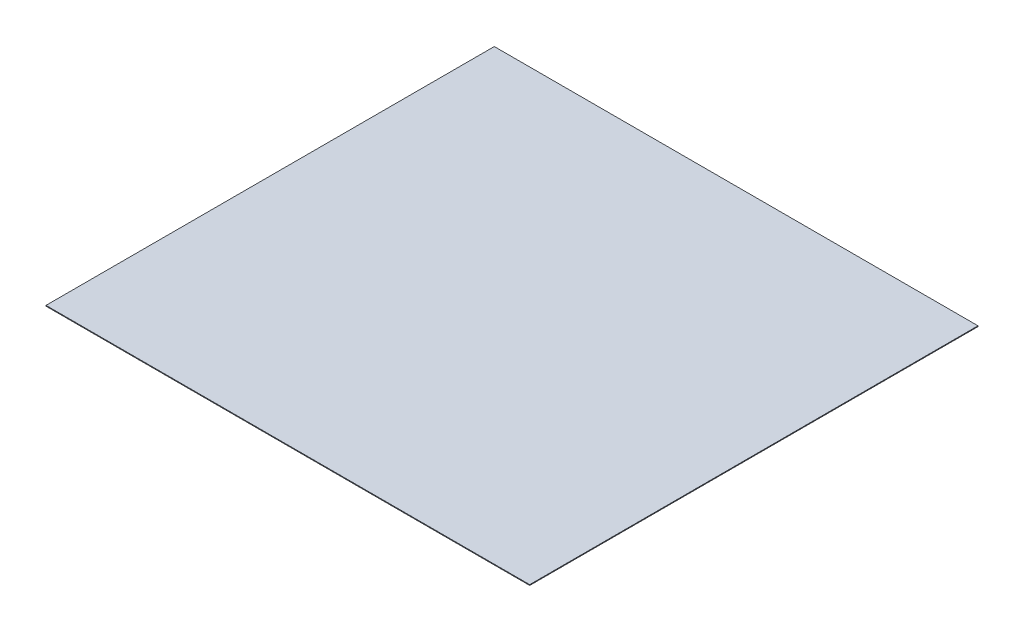
SolidWorks part; units mm, degrees
ref_plane "Front Plane" through (0, 0, 0) normal (0, 0, 1) x (1, 0, 0)
ref_plane "Top Plane" through (0, 0, 0) normal (0, 1, 0) x (1, 0, 0)
ref_plane "Right Plane" through (0, 0, 0) normal (1, 0, 0) x (0, 0, -1)
sketch "Sketch1" plane through (0, 0, 0) normal (0, 1, 0) x (1, 0, 0)
  line L0 (-1282.1828, -917.2453) -> (800.6172, -917.2453)
  line L1 (-1282.1828, -917.2453) -> (-1282.1828, 1013.1547)
  line L2 (-1282.1828, 1013.1547) -> (800.6172, 1013.1547)
  line L3 (800.6172, -917.2453) -> (800.6172, 1013.1547)
  dimension "D1" = 1930.4
  dimension "D2" = 2082.8
extrude "Boss-Extrude1" add sketch "Sketch1" along normal blind 3.175
